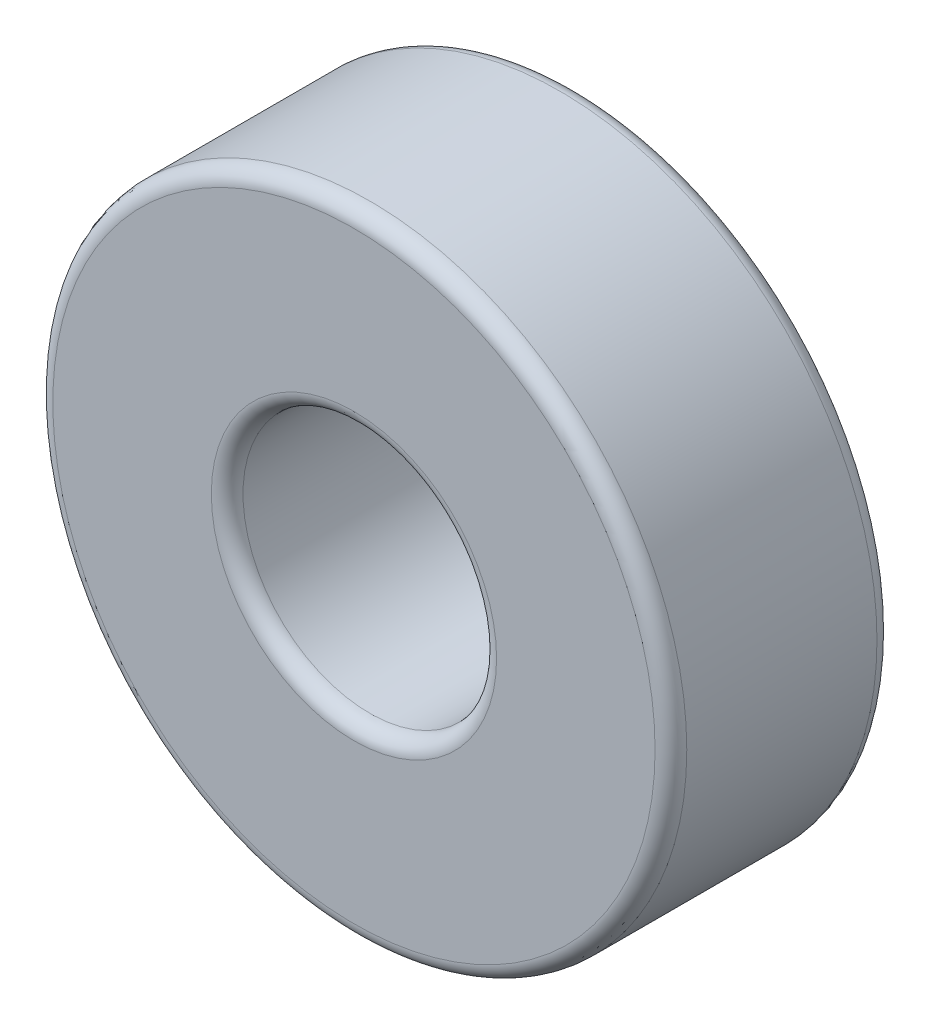
SolidWorks part; units mm, degrees
ref_plane "Front Plane" through (0, 0, 0) normal (0, 0, 1) x (1, 0, 0)
ref_plane "Top Plane" through (0, 0, 0) normal (0, 1, 0) x (1, 0, 0)
ref_plane "Right Plane" through (0, 0, 0) normal (1, 0, 0) x (0, 0, -1)
sketch "Sketch1" plane through (0, 0, 0) normal (0, 0, 1) x (1, 0, 0)
  circle A0 centre (0, 0) radius 10
  circle A1 centre (0, 0) radius 4
  dimension "D1" = 20
  dimension "D2" = 8
extrude "Boss-Extrude1" add sketch "Sketch1" along normal blind 7
fillet "Fillet2" radius 0.5 4 edges at (4, 0, 0) (4, 0, 7) (10, 0, 0) (10, 0, 7)
